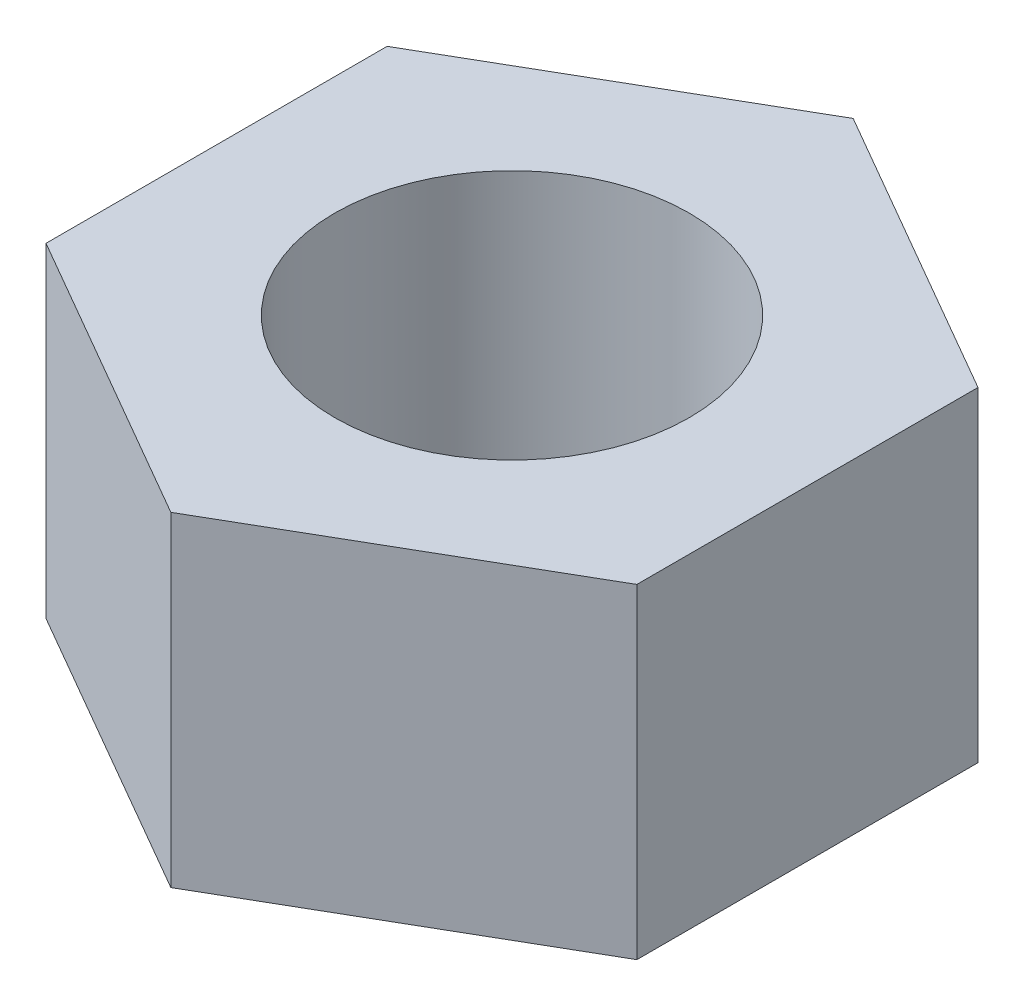
SolidWorks part; units mm, degrees
ref_plane "Спереди" through (0, 0, 0) normal (0, 0, 1) x (1, 0, 0)
ref_plane "Сверху" through (0, 0, 0) normal (0, 1, 0) x (1, 0, 0)
ref_plane "Справа" through (0, 0, 0) normal (1, 0, 0) x (0, 0, -1)
sketch "Эскиз1" plane through (0, 0, 0) normal (0, 1, 0) x (1, 0, 0)
  line L1 (0, -5.7735) -> (5, -2.8868)
  line L2 (5, -2.8868) -> (5, 2.8868)
  line L3 (5, 2.8868) -> (0, 5.7735)
  line L4 (0, 5.7735) -> (-5, 2.8868)
  line L5 (-5, 2.8868) -> (-5, -2.8868)
  line L6 (-5, -2.8868) -> (0, -5.7735)
  circle A0 centre (0, 0) radius 5 construction
  circle A1 centre (0, 0) radius 3
extrude "Вытянуть1" add sketch "Эскиз1" along normal blind 5.5
